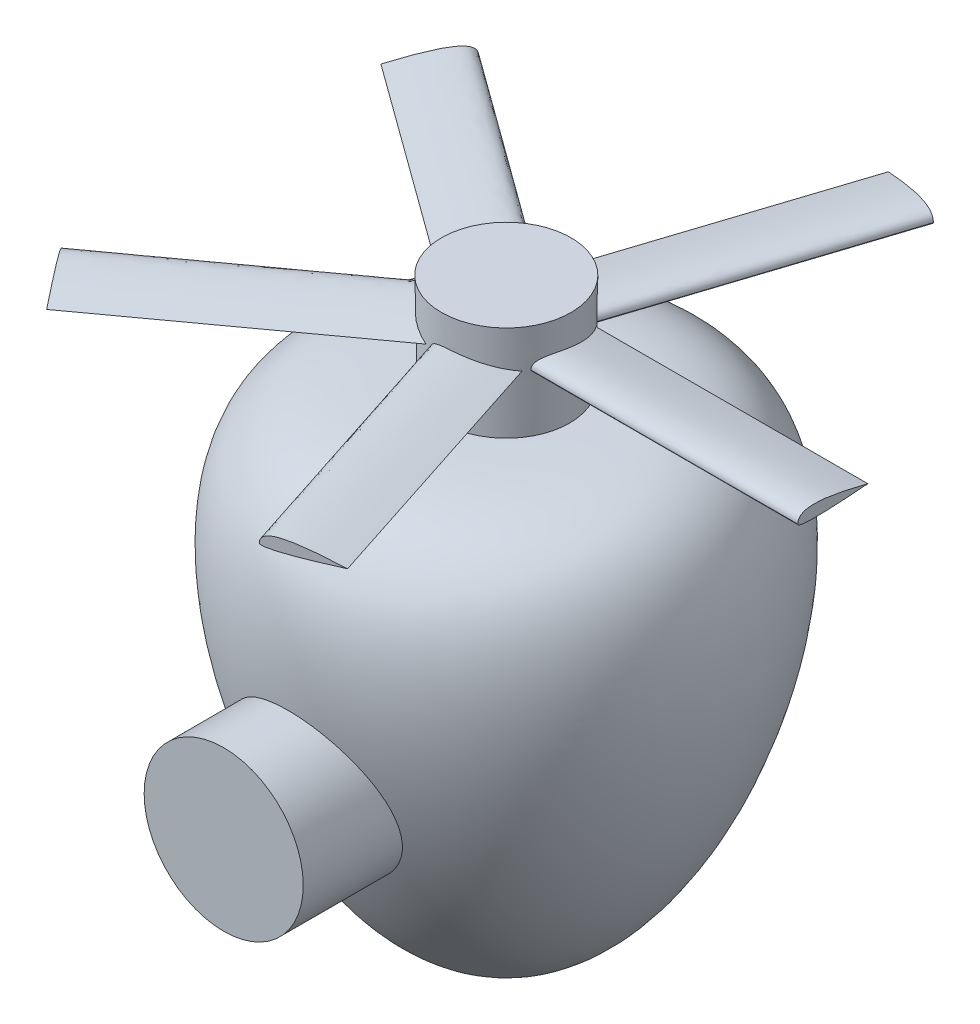
SolidWorks part; units mm, degrees
ref_plane "Front Plane" through (0, 0, 0) normal (0, 0, 1) x (1, 0, 0)
ref_plane "Top Plane" through (0, 0, 0) normal (0, 1, 0) x (1, 0, 0)
ref_plane "Right Plane" through (0, 0, 0) normal (1, 0, 0) x (0, 0, -1)
sketch "Sketch1" plane through (0, 0, 0) normal (0, 0, 1) x (1, 0, 0)
  line L0 (0, 0) -> (0, 540.2222) construction
  line L1 (39.8608, 304.8) -> (137.7269, 304.8) construction
  line L2 (137.7269, 304.8) -> (184.8476, 294.0899) construction
  line L3 (184.8476, 294.0899) -> (127, 0) construction
  line L4 (127, 0) -> (0, 0) construction
  line L5 (39.8608, 304.8) -> (0, 264.9392)
  line L6 (0, 0) -> (0, 264.9392)
  spline S0 degree 4 poles (39.8608, 304.8) (137.7269, 304.8) (184.8476, 294.0899) (127, 0) (0, 0) knots 0 0 0 0 0 1 1 1 1 1
  dimension "D1" = 304.8
  dimension "D2" = 127
  dimension "D3" = 39.8608
revolve "Revolve1" add sketch "Sketch1" angle 360 about L0
sketch "Sketch2" plane through (0, 0, 0) normal (1, 0, 0) x (0, 0, -1)
  line L0 (39.8608, 304.8) -> (40.7526, 365.5211)
  line L1 (40.7526, 365.5211) -> (0, 365.5211)
  line L2 (39.8608, 304.8) -> (0, 264.9392)
  line L3 (0, 264.9392) -> (39.8608, 304.8) construction
  line L4 (0, 365.5211) -> (0, 264.9392) construction
  line L5 (0, 365.5211) -> (0, 264.9392)
revolve "Revolve2" add sketch "Sketch2" angle 360 about L4
sketch "Sketch3" plane through (0, 0, 0) normal (1, 0, 0) x (0, 0, -1)
  line L7 (24.2929, 341.3155) -> (-19.7529, 341.3155) construction
  line L8 (0, 406.1724) -> (0, 353.1218) construction
  line L9 (-19.7529, 341.3155) -> (-19.7529, 350.8622) construction
  line L10 (-19.7529, 350.8622) -> (0.4086, 347.398) construction
  line L11 (0.4086, 347.398) -> (24.2929, 341.3155) construction
  line L12 (-19.7529, 341.3155) -> (-19.7529, 337.7618) construction
  line L13 (-19.7529, 337.7618) -> (24.2929, 341.3155) construction
  line L14 (40.7526, 365.5211) -> (-40.7526, 365.5211) construction
  spline S2 degree 3 poles (-19.7529, 341.3155) (-19.7529, 350.8622) (0.4086, 347.398) (24.2929, 341.3155) knots 0 0 0 0 1 1 1 1
  spline S3 degree 2 poles (-19.7529, 341.3155) (-19.7529, 337.7618) (24.2929, 341.3155) knots 0 0 0 1 1 1
  point P9 (-1.8614, 491.7703)
  point P10 (-21.9615, 482.1346)
  point P16 (2.27, 341.3155)
  point P21 (-0.4337, 353.1218)
extrude "Boss-Extrude1" add sketch "Sketch3" along normal blind 203.2
pattern_circular "CirPattern1" count 5 over 360 about axis through (0, 365.5211, 0) along (0, 1, 0) of "Boss-Extrude1"
sketch "Sketch4" plane through (0, 0, 0) normal (0, 0, 1) x (1, 0, 0)
  circle A0 centre (0, 146.9092) radius 50.0442
extrude "Boss-Extrude2" add sketch "Sketch4" along normal blind 177.8 contours A0
